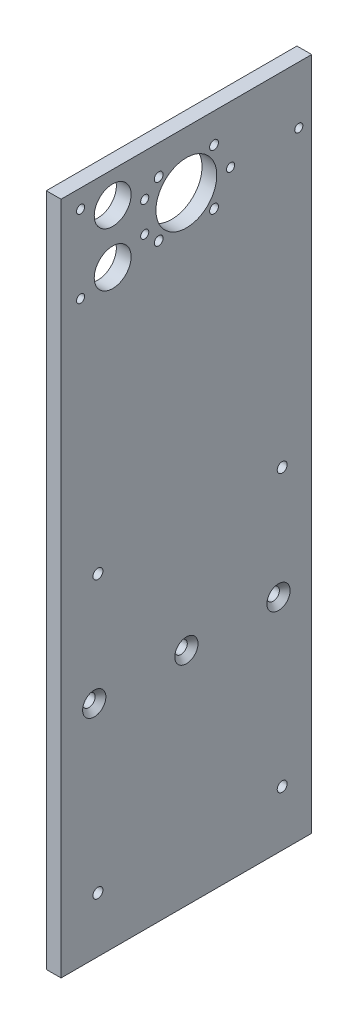
SolidWorks part; units mm, degrees
ref_plane "前基準面" through (0, 0, 0) normal (0, 0, 1) x (1, 0, 0)
ref_plane "上基準面" through (0, 0, 0) normal (0, 1, 0) x (1, 0, 0)
ref_plane "右基準面" through (0, 0, 0) normal (1, 0, 0) x (0, 0, -1)
sketch "草圖1" plane through (0, 0, 0) normal (1, 0, 0) x (0, 0, -1)
  line L1 (-34, -90) -> (34, -90)
  line L2 (-34, -90) -> (-34, 90)
  line L3 (-34, 90) -> (34, 90)
  line L4 (34, -90) -> (34, 90)
  line L5 (-34, -90) -> (34, 90) construction
  line L6 (-34, 90) -> (34, -90) construction
  point P0 (0, 0)
  dimension "D1" = 180
  dimension "D2" = 68
extrude "填料-伸長1" add sketch "草圖1" along normal blind 4
hole_wizard "M2 錐坑平頭螺釘的錐孔1" positions "草圖2" profile "草圖3" countersink size "M2" standard "ISO"
sketch "草圖2" plane through (0, 0, 0) normal (-1, 0, 0) x (0, 0, 1)
  line L0 (-7.5, 85) -> (7.5, 85) construction
  line L2 (0, 85) -> (0, 0) construction
  line L4 (-34, 90) -> (34, 90) construction
  point P0 (-7.5, 85)
  point P2 (-7.5, 70)
  point P4 (7.5, 85)
  point P6 (7.5, 70)
  dimension "D1" = 15
  dimension "D2" = 15
  dimension "D3" = 5
sketch "草圖3" plane through (0, 85, -7.5) normal (0, 1, 0) x (0, 0, 1)
  line L0 (0, 0) -> (0, 8.221)
  line L1 (0, 8.221) -> (1.2, 7.5)
  line L2 (1.2, 7.5) -> (1.2, 1)
  line L3 (1.2, 1) -> (2.2, 0)
  line L5 (2.2, 0) -> (0, 0)
  line L6 (-1.2, 1) -> (-2.2, 0) construction
  line L10 (0, 8.221) -> (-1.2, 7.5) construction
  line L11 (0, -6.35) -> (0, 107.95) construction
  dimension "鑽孔直徑" = 2.4
  dimension "鑽孔深度" = 7.5
  dimension "近端錐孔直徑" = 4.4
  dimension "近端錐孔角度" = 90
  dimension "導頭角度" = 118
sketch "草圖4" plane through (0, 0, 0) normal (-1, 0, 0) x (0, 0, 1)
  line L0 (-7.5, 85) -> (7.5, 70) construction
  line L1 (-7.5, 70) -> (7.5, 85) construction
  circle A0 centre (0, 77.5) radius 8.25
  dimension "D1" = 16.5
extrude "除料-伸長1" cut sketch "草圖4" against normal through all
hole_wizard "M3 錐坑平頭螺釘的錐孔1" positions "草圖7" profile "草圖8" countersink size "M3" standard "ISO"
sketch "草圖7" plane through (4, 0, 0) normal (1, 0, 0) x (0, 0, -1)
  line L0 (-34, -90) -> (34, -90) construction
  point P0 (-25, -30)
  point P2 (0, -30)
  point P4 (25, -30)
  dimension "D1" = 25
  dimension "D2" = 25
  dimension "D3" = 60
sketch "草圖8" plane through (4, -30, 25) normal (0, 1, 0) x (0, 0, -1)
  line L0 (0, 0) -> (0, 8.5215)
  line L1 (0, 8.5215) -> (1.7, 7.5)
  line L2 (1.7, 7.5) -> (1.7, 1.45)
  line L3 (1.7, 1.45) -> (3.15, 0)
  line L5 (3.15, 0) -> (0, 0)
  line L6 (-1.7, 1.45) -> (-3.15, 0) construction
  line L10 (0, 8.5215) -> (-1.7, 7.5) construction
  line L11 (0, -6.35) -> (0, 107.95) construction
  dimension "鑽孔直徑" = 3.4
  dimension "鑽孔深度" = 7.5
  dimension "近端錐孔直徑" = 6.3
  dimension "近端錐孔角度" = 90
  dimension "導頭角度" = 118
hole_wizard "M2.5 螺紋孔1" [suppressed] positions "草圖9" profile "草圖10" tap size "M2.5" standard "ISO"
sketch "草圖9" plane through (4, 0, 0) normal (1, 0, 0) x (0, 0, -1)
  line L0 (-9.25, 53.5) -> (9.25, 53.5) construction
  line L2 (0, 67.5) -> (0, 53.5) construction
  line L4 (-30, 57.5) -> (30, 57.5) construction
  line L5 (-30, 80) -> (-30, -80) construction
  line L6 (30, -80) -> (30, 80) construction
  circle A0 centre (0, 67.5) radius 8.25 construction
  point P0 (-9.25, 53.5)
  point P2 (9.25, 53.5)
  dimension "D2" = 10
  dimension "D1" = 18.5
  dimension "D3" = 4
sketch "草圖10" plane through (4, 53.5, 9.25) normal (0, 1, 0) x (0, 0, -1)
  line L0 (0, 0) -> (0, 4)
  line L1 (0, 4) -> (1.025, 4)
  line L2 (1.025, 4) -> (1.025, 0.25)
  line L3 (1.025, 0.25) -> (1.275, 0)
  line L5 (1.275, 0) -> (0, 0)
  line L6 (-1.025, 0.25) -> (-1.275, 0) construction
  line L11 (0, -6.35) -> (0, 107.95) construction
  dimension "貫穿螺孔鑽直徑" = 2.05
  dimension "貫穿螺孔鑽深度" = 4
  dimension "近端錐孔直徑" = 2.55
  dimension "近端錐孔角度" = 90
cosmetic thread "鑽孔螺紋1" [suppressed] parameters "D2"=2.5
cosmetic thread "鑽孔螺紋2" [suppressed] parameters "D2"=2.5
sketch "草圖11" [suppressed] plane through (4, 0, 0) normal (1, 0, 0) x (0, 0, -1)
  line L0 (0, 53.5) -> (-9.25, 53.5) construction
  circle A0 centre (0, 53.5) radius 5
  dimension "D1" = 10
extrude "除料-伸長2" [suppressed] cut sketch "草圖11" against normal through all
hole_wizard "Ø1.0mm 定位孔1" positions "草圖12" profile "草圖13" hole size "Ø1.0" standard "ISO" end condition through all
sketch "草圖12" plane through (4, 0, 0) normal (1, 0, 0) x (0, 0, -1)
  line L0 (0, 77.5) -> (12, 77.5) construction
  line L2 (15, 90) -> (15, -90) construction
  line L3 (34, 90) -> (-34, 90) construction
  line L4 (-34, -90) -> (34, -90) construction
  point P0 (12, 77.5)
  point P2 (30.5, 77.5)
  dimension "D1" = 18.5
  dimension "D2" = 15
  dimension "D3" = 3
sketch "草圖13" plane through (4, 77.5, -12) normal (0, 1, 0) x (0, 0, -1)
  line L0 (0, 0) -> (0, 4)
  line L1 (0, 4) -> (1.1, 4)
  line L2 (1.1, 4) -> (1.1, 0)
  line L5 (1.1, 0) -> (0, 0)
  line L11 (0, -6.35) -> (0, 107.95) construction
  dimension "貫穿孔直徑" = 2.2
  dimension "貫穿孔深度" = 4
sketch "草圖14" [suppressed] plane through (4, 0, 0) normal (1, 0, 0) x (0, 0, -1)
  line L0 (0, 77.5) -> (-28.6606, 87.9316)
  line L1 (0, 77.5) -> (-28.6606, 67.0684)
  line L2 (0, 77.5) -> (-30.5, 77.5)
  circle A0 centre (0, 77.5) radius 12
  circle A1 centre (0, 77.5) radius 30.5
  circle A2 centre (0, 77.5) radius 21.25
  point P7 (-11.2763, 81.6042)
  point P11 (-11.2763, 73.3958)
  point P12 (-19.9685, 70.2321)
  point P14 (-19.9685, 84.7679)
  dimension "D1" = 9.25
  dimension "D2" = 20
  dimension "D3" = 20
hole_wizard "M2.5 螺紋孔3" [suppressed] positions "草圖15" profile "草圖16" tap size "M2.5" standard "ISO"
sketch "草圖15" [suppressed] plane through (4, 0, 0) normal (1, 0, 0) x (0, 0, -1)
  line L0 (0, 77.5) -> (-28.6606, 87.9316) construction
  line L1 (0, 77.5) -> (-28.6606, 67.0684) construction
  circle A0 centre (0, 77.5) radius 12 construction
  point P0 (-11.2763, 81.6042)
  point P6 (-28.6606, 87.9316)
  point P10 (-11.2763, 73.3958)
  point P14 (-28.6606, 67.0684)
sketch "草圖16" plane through (4, 81.6042, 11.2763) normal (0, 1, 0) x (0, 0, -1)
  line L0 (0, 0) -> (0, 6.9659)
  line L1 (0, 6.9659) -> (1.025, 6.35)
  line L2 (1.025, 6.35) -> (1.025, 0.25)
  line L3 (1.025, 0.25) -> (1.275, 0)
  line L5 (1.275, 0) -> (0, 0)
  line L6 (-1.025, 0.25) -> (-1.275, 0) construction
  line L10 (0, 6.9659) -> (-1.025, 6.35) construction
  line L11 (0, -6.35) -> (0, 107.95) construction
  dimension "螺孔鑽直徑" = 2.05
  dimension "螺孔鑽深度" = 6.35
  dimension "近端錐孔直徑" = 2.55
  dimension "近端錐孔角度" = 90
  dimension "導頭角度" = 118
cosmetic thread "鑽孔螺紋5" [suppressed] parameters "D1"=4, "D2"=2.5
cosmetic thread "鑽孔螺紋6" [suppressed] parameters "D1"=4, "D2"=2.5
cosmetic thread "鑽孔螺紋7" [suppressed] parameters "D1"=4, "D2"=2.5
cosmetic thread "鑽孔螺紋8" [suppressed] parameters "D1"=4, "D2"=2.5
sketch "草圖17" plane through (0, 90, 0) normal (0, 1, 0) x (1, 0, 0)
  line L1 (0, 34) -> (4, 34)
  line L2 (0, 34) -> (0, -34)
  line L3 (0, -34) -> (4, -34)
  line L4 (4, 34) -> (4, -34)
extrude "填料-伸長2" add sketch "草圖17" along normal blind 3
sketch "草圖18" [suppressed] plane through (0, 0, 0) normal (-1, 0, 0) x (0, 0, 1)
  line L0 (-12, 77.5) -> (-30.5, 77.5) construction
  circle A0 centre (0, 77.5) radius 30.5 construction
  circle A1 centre (-21.25, 77.5) radius 5
  dimension "D1" = 10
extrude "除料-伸長3" [suppressed] cut sketch "草圖18" against normal through all
hole_wizard "Ø1.0mm 定位孔2" positions "草圖19" profile "草圖20" hole size "Ø1.0" standard "ISO"
sketch "草圖19" plane through (0, 0, 0) normal (-1, 0, 0) x (0, 0, 1)
  line L0 (34, 93) -> (34, -90) construction
  line L1 (-34, 93) -> (34, 93) construction
  point P0 (28.7, 88)
  point P2 (28.7, 67)
  point P4 (11.3, 81.6)
  point P6 (11.3, 73.4)
  dimension "D1" = 5.3
  dimension "D2" = 22.7
  dimension "D3" = 5
  dimension "D4" = 26
  dimension "D5" = 11.4
  dimension "D6" = 19.6
sketch "草圖20" plane through (0, 88, 28.7) normal (0, 1, 0) x (0, 0, 1)
  line L0 (0, 0) -> (0, 7.0109)
  line L1 (0, 7.0109) -> (1.1, 6.35)
  line L2 (1.1, 6.35) -> (1.1, 0)
  line L5 (1.1, 0) -> (0, 0)
  line L10 (0, 7.0109) -> (-1.1, 6.35) construction
  line L11 (0, -6.35) -> (0, 107.95) construction
  dimension "鑽孔直徑" = 2.2
  dimension "鑽孔深度" = 6.35
  dimension "導頭角度" = 118
sketch "草圖21" plane through (0, 0, 0) normal (-1, 0, 0) x (0, 0, 1)
  line L0 (34, 93) -> (34, -90) construction
  line L1 (-34, 93) -> (34, 93) construction
  circle A0 centre (20, 84.6) radius 5
  circle A1 centre (20, 70) radius 5
  dimension "D1" = 10
  dimension "D3" = 8.4
  dimension "D2" = 14
  dimension "D4" = 23
extrude "除料-伸長4" cut sketch "草圖21" against normal through all
hole_wizard "Ø1.0mm 定位孔3" positions "草圖22" profile "草圖23" hole size "Ø1.0" standard "ISO"
sketch "草圖22" plane through (0, -90, 0) normal (0, -1, 0) x (-1, 0, 0)
  line L0 (-2, -34) -> (-2, -25) construction
  line L1 (-4, -34) -> (0, -34) construction
  point P0 (-2, 0)
  point P2 (-2, -25)
  point P4 (-2, 25)
  dimension "D1" = 25
  dimension "D2" = 25
sketch "草圖23" plane through (2, -90, 0) normal (1, 0, 0) x (0, 0, -1)
  line L0 (0, 0) -> (0, 7.9109)
  line L1 (0, 7.9109) -> (1.1, 7.25)
  line L2 (1.1, 7.25) -> (1.1, 0)
  line L5 (1.1, 0) -> (0, 0)
  line L10 (0, 7.9109) -> (-1.1, 7.25) construction
  line L11 (0, -6.35) -> (0, 107.95) construction
  dimension "鑽孔直徑" = 2.2
  dimension "鑽孔深度" = 7.25
  dimension "導頭角度" = 118
hole_wizard "Ø1.0mm 定位孔4" positions "草圖24" profile "草圖25" hole size "Ø1.0" standard "ISO" end condition through all
sketch "草圖24" plane through (4, 0, 0) normal (1, 0, 0) x (0, 0, -1)
  line L0 (34, -90) -> (34, 93) construction
  line L1 (-34, -90) -> (34, -90) construction
  point P0 (26, -75)
  point P2 (26, 0)
  point P4 (-24, 0)
  point P6 (-24, -75)
  dimension "D1" = 8
  dimension "D2" = 50
  dimension "D3" = 15
  dimension "D4" = 75
sketch "草圖25" plane through (4, -75, -26) normal (0, 1, 0) x (0, 0, -1)
  line L0 (0, 0) -> (0, 4)
  line L1 (0, 4) -> (1.35, 4)
  line L2 (1.35, 4) -> (1.35, 0)
  line L5 (1.35, 0) -> (0, 0)
  line L11 (0, -6.35) -> (0, 107.95) construction
  dimension "貫穿孔直徑" = 2.7
  dimension "貫穿孔深度" = 4
